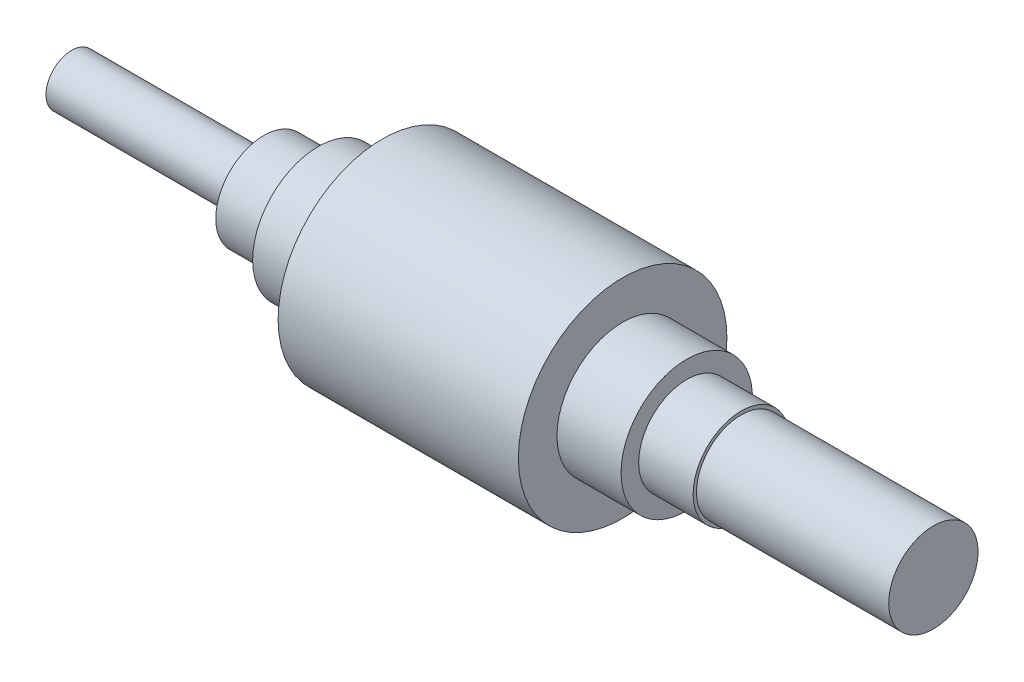
SolidWorks part; units mm, degrees
ref_plane "Ön Düzlem" through (0, 0, 0) normal (0, 0, 1) x (1, 0, 0)
ref_plane "Üst Düzlem" through (0, 0, 0) normal (0, 1, 0) x (1, 0, 0)
ref_plane "Sağ Düzlem" through (0, 0, 0) normal (1, 0, 0) x (0, 0, -1)
sketch "Çizim1" plane through (0, 0, 0) normal (0, 0, 1) x (1, 0, 0)
  line L1 (30, 7.5) -> (38.5, 7.5)
  line L2 (38.5, 7.5) -> (38.5, 10.25)
  line L3 (38.5, 10.25) -> (48.5, 10.25)
  line L4 (48.5, 10.25) -> (48.5, 16.275)
  line L5 (48.5, 16.275) -> (86, 16.275)
  line L6 (86, 16.275) -> (86, 10.25)
  line L7 (86, 10.25) -> (96, 10.25)
  line L8 (96, 10.25) -> (96, 7.5)
  line L10 (134.5, 6.975) -> (134.5, 0)
  line L11 (0, 0) -> (50000, 0) construction
  line L12 (0, 0) -> (134.5, 0)
  line L13 (96, 7.5) -> (104.5, 7.5)
  line L14 (104.5, 7.5) -> (104.5, 6.975)
  line L15 (104.5, 6.975) -> (134.5, 6.975)
  line L16 (30, 7.5) -> (30, 4)
  line L17 (30, 4) -> (0, 4)
  line L18 (0, 4) -> (0, 0)
  dimension "D2" = 7.5
  dimension "D3" = 10
  dimension "D4" = 10.25
  dimension "D5" = 37.5
  dimension "D6" = 6.975
  dimension "D7" = 7.5
  dimension "D8" = 16.275
  dimension "D9" = 10
  dimension "D10" = 8.5
  dimension "D11" = 10.25
  dimension "D12" = 30
  dimension "D13" = 8.5
  dimension "D14" = 30
  dimension "D15" = 4
revolve "Döndür1" add sketch "Çizim1" angle 360 about L11
